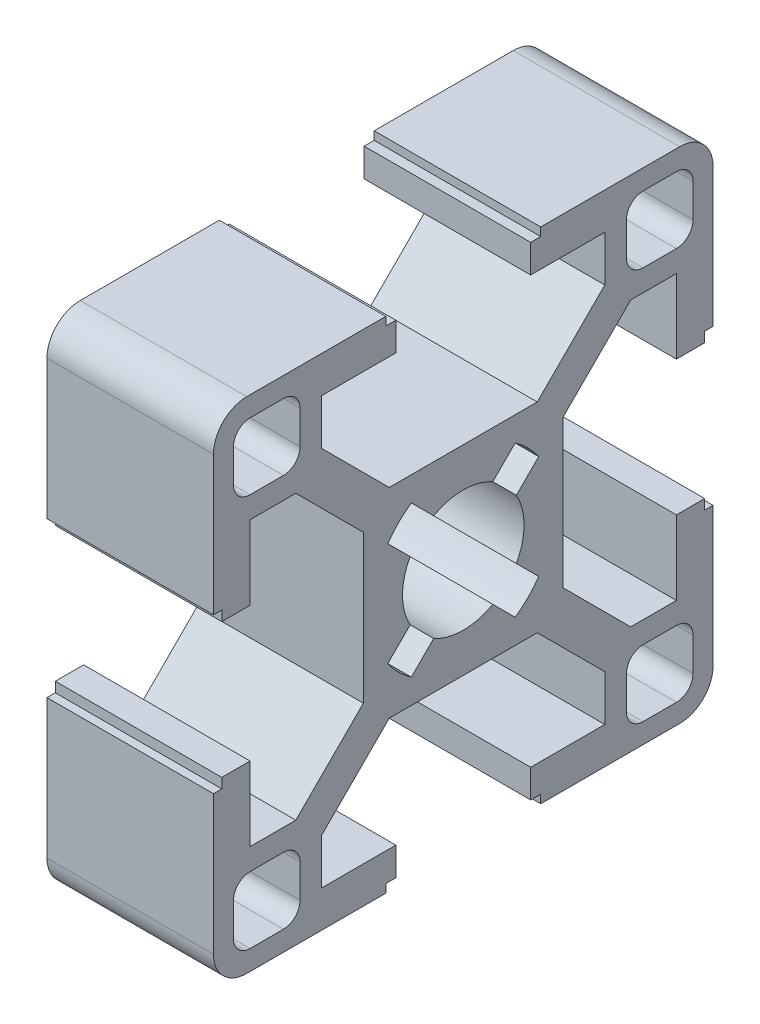
SolidWorks part; units mm, degrees
ref_plane "Ebene vorne" through (0, 0, 0) normal (0, 0, 1) x (1, 0, 0)
ref_plane "Ebene oben" through (0, 0, 0) normal (0, 1, 0) x (1, 0, 0)
ref_plane "Ebene rechts" through (0, 0, 0) normal (1, 0, 0) x (0, 0, -1)
sketch "Skizze1" plane through (0, 0, 0) normal (1, 0, 0) x (0, 0, -1)
  line L0 (8.5, 10.0556) -> (4.4444, 6)
  line L1 (13, 15) -> (-13, 15)
  line L2 (15, 13) -> (15, -13)
  line L3 (13, -15) -> (-13, -15)
  line L4 (-15, 13) -> (-15, -13)
  line L5 (15, 15) -> (-15, -15) construction
  line L6 (15, -15) -> (-15, 15) construction
  line L7 (6, 6) -> (-6, 6)
  line L8 (6, 6) -> (6, -6)
  line L9 (6, -6) -> (-6, -6)
  line L10 (-6, 6) -> (-6, -6)
  line L11 (6, 6) -> (-6, -6) construction
  line L12 (6, -6) -> (-6, 6) construction
  line L13 (8.5, 12.8) -> (-8.5, 12.8)
  line L14 (8.5, 12.8) -> (8.5, 6)
  line L15 (8.5, 6) -> (-8.5, 6)
  line L16 (-8.5, 12.8) -> (-8.5, 6)
  line L17 (4.05, 15) -> (-4.05, 15)
  line L18 (4.05, 15) -> (4.05, 12.8)
  line L19 (4.05, 12.8) -> (-4.05, 12.8)
  line L20 (-4.05, 15) -> (-4.05, 12.8)
  line L21 (-8.5, 10.0556) -> (-4.4444, 6)
  line L22 (3.1172, 4.5314) -> (1.7751, 3.1893)
  line L23 (-3.1172, 4.5314) -> (-1.7751, 3.1893)
  line L24 (15, -4.05) -> (12.8, -4.05)
  line L25 (4.05, 15) -> (4.6516, 15)
  line L26 (4.05, 15) -> (4.05, 14.5)
  line L27 (4.05, 14.5) -> (4.6516, 14.5)
  line L28 (4.6516, 15) -> (4.6516, 14.5)
  line L29 (-4.05, 15) -> (-4.6516, 15)
  line L30 (-4.05, 15) -> (-4.05, 14.5)
  line L31 (-4.05, 14.5) -> (-4.6516, 14.5)
  line L32 (-4.6516, 15) -> (-4.6516, 14.5)
  line L33 (15, -4.6516) -> (14.5, -4.6516)
  line L34 (14.5, -4.05) -> (14.5, -4.6516)
  line L35 (14.5, 4.05) -> (14.5, 4.6516)
  line L36 (15, 4.6516) -> (14.5, 4.6516)
  line L37 (15, 4.05) -> (12.8, 4.05)
  line L38 (12.8, 8.5) -> (6, 8.5)
  line L39 (12.8, -8.5) -> (12.8, 8.5)
  line L40 (12.8, -8.5) -> (6, -8.5)
  line L41 (10.0556, -8.5) -> (6, -4.4444)
  line L42 (10.0556, 8.5) -> (6, 4.4444)
  line L43 (4.5314, -3.1172) -> (3.1893, -1.7751)
  line L44 (4.5314, 3.1172) -> (3.1893, 1.7751)
  line L45 (-4.05, -15) -> (-4.05, -12.8)
  line L46 (-4.6516, -15) -> (-4.6516, -14.5)
  line L47 (-4.05, -14.5) -> (-4.6516, -14.5)
  line L48 (4.05, -14.5) -> (4.6516, -14.5)
  line L49 (4.6516, -15) -> (4.6516, -14.5)
  line L50 (4.05, -15) -> (4.05, -12.8)
  line L51 (8.5, -12.8) -> (8.5, -6)
  line L52 (-8.5, -12.8) -> (8.5, -12.8)
  line L53 (-8.5, -12.8) -> (-8.5, -6)
  line L54 (-8.5, -10.0556) -> (-4.4444, -6)
  line L55 (8.5, -10.0556) -> (4.4444, -6)
  line L56 (-3.1172, -4.5314) -> (-1.7751, -3.1893)
  line L57 (3.1172, -4.5314) -> (1.7751, -3.1893)
  line L58 (-15, 4.05) -> (-12.8, 4.05)
  line L59 (-15, 4.6516) -> (-14.5, 4.6516)
  line L60 (-14.5, 4.05) -> (-14.5, 4.6516)
  line L61 (-14.5, -4.05) -> (-14.5, -4.6516)
  line L62 (-15, -4.6516) -> (-14.5, -4.6516)
  line L63 (-15, -4.05) -> (-12.8, -4.05)
  line L64 (-12.8, -8.5) -> (-6, -8.5)
  line L65 (-12.8, 8.5) -> (-12.8, -8.5)
  line L66 (-12.8, 8.5) -> (-6, 8.5)
  line L67 (-10.0556, 8.5) -> (-6, 4.4444)
  line L68 (-10.0556, -8.5) -> (-6, -4.4444)
  line L69 (-4.5314, 3.1172) -> (-3.1893, 1.7751)
  line L70 (-4.5314, -3.1172) -> (-3.1893, -1.7751)
  line L71 (6, -8.5) -> (6, 8.5)
  line L72 (-8.5, -6) -> (8.5, -6)
  line L73 (-6, 8.5) -> (-6, -8.5)
  line L75 (12.8, 13.8) -> (10.8, 13.8)
  line L76 (13.8, 12.8) -> (13.8, 10.8)
  line L77 (12.8, 9.8) -> (10.8, 9.8)
  line L78 (9.8, 12.8) -> (9.8, 10.8)
  line L79 (13.8, 13.8) -> (9.8, 9.8) construction
  line L80 (13.8, 9.8) -> (9.8, 13.8) construction
  line L81 (-10.8, 13.8) -> (-12.8, 13.8)
  line L82 (-9.8, 12.8) -> (-9.8, 10.8)
  line L83 (-10.8, 9.8) -> (-12.8, 9.8)
  line L84 (-13.8, 12.8) -> (-13.8, 10.8)
  line L85 (-9.8, 13.8) -> (-13.8, 9.8) construction
  line L86 (-9.8, 9.8) -> (-13.8, 13.8) construction
  line L87 (12.8, -9.8) -> (10.8, -9.8)
  line L88 (13.8, -10.8) -> (13.8, -12.8)
  line L89 (12.8, -13.8) -> (10.8, -13.8)
  line L90 (9.8, -10.8) -> (9.8, -12.8)
  line L91 (13.8, -9.8) -> (9.8, -13.8) construction
  line L92 (13.8, -13.8) -> (9.8, -9.8) construction
  line L93 (-10.8, -9.8) -> (-12.8, -9.8)
  line L94 (-9.8, -10.8) -> (-9.8, -12.8)
  line L95 (-10.8, -13.8) -> (-12.8, -13.8)
  line L96 (-13.8, -10.8) -> (-13.8, -12.8)
  line L97 (-9.8, -9.8) -> (-13.8, -13.8) construction
  line L98 (-9.8, -13.8) -> (-13.8, -9.8) construction
  arc A0 (13, -15) -> (15, -13) centre (13, -13) ccw
  arc A1 (-13, -15) -> (-15, -13) centre (-13, -13) cw
  arc A2 (-15, 13) -> (-13, 15) centre (-13, 13) cw
  arc A3 (13, 15) -> (15, 13) centre (13, 13) cw
  circle A4 centre (0, 0) radius 3.65
  circle A5 centre (0, 0) radius 5.5
  circle A6 centre (0, 0) radius 3.65
  circle A7 centre (0, 0) radius 3.65
  circle A8 centre (0, 0) radius 3.65
  arc A9 (12.8, -13.8) -> (13.8, -12.8) centre (12.8, -12.8) ccw
  arc A10 (13.8, -10.8) -> (12.8, -9.8) centre (12.8, -10.8) ccw
  arc A11 (9.8, -12.8) -> (10.8, -13.8) centre (10.8, -12.8) ccw
  arc A12 (9.8, -10.8) -> (10.8, -9.8) centre (10.8, -10.8) cw
  arc A13 (-10.8, -13.8) -> (-9.8, -12.8) centre (-10.8, -12.8) ccw
  arc A14 (-10.8, -9.8) -> (-9.8, -10.8) centre (-10.8, -10.8) cw
  arc A15 (-13.8, -12.8) -> (-12.8, -13.8) centre (-12.8, -12.8) ccw
  arc A16 (-13.8, -10.8) -> (-12.8, -9.8) centre (-12.8, -10.8) cw
  arc A17 (-12.8, 9.8) -> (-13.8, 10.8) centre (-12.8, 10.8) cw
  arc A18 (-10.8, 9.8) -> (-9.8, 10.8) centre (-10.8, 10.8) ccw
  arc A19 (-13.8, 12.8) -> (-12.8, 13.8) centre (-12.8, 12.8) cw
  arc A20 (-10.8, 13.8) -> (-9.8, 12.8) centre (-10.8, 12.8) cw
  arc A21 (13.8, 10.8) -> (12.8, 9.8) centre (12.8, 10.8) cw
  arc A22 (10.8, 9.8) -> (9.8, 10.8) centre (10.8, 10.8) cw
  arc A23 (10.8, 13.8) -> (9.8, 12.8) centre (10.8, 12.8) ccw
  arc A24 (12.8, 13.8) -> (13.8, 12.8) centre (12.8, 12.8) cw
  point P0 (0, 0)
  point P33 (0, 12.8)
  point P34 (0, 15)
  point P36 (0, 12.8)
  point P50 (11.8, 11.8)
  point P122 (0, 0)
  point P125 (-11.8, 11.8)
  point P129 (0, 0)
  point P131 (11.8, -11.8)
  point P136 (-11.8, -11.8)
  point P141 (0, 0)
  point P142 (0, 0)
  point P143 (0, 0)
  point P144 (0, 0)
  dimension "D2" = 2
  dimension "D3" = 7.3
  dimension "D4" = 11
  dimension "D20" = 1
  dimension "D1" = 30
  dimension "D5" = 12
  dimension "D6" = 17
  dimension "D7" = 8.1
  dimension "D8" = 2.2
  dimension "D9" = 9
  dimension "D10" = 1.1
  dimension "D11" = 1.1
  dimension "D12" = 1
  dimension "D13" = 1
  dimension "D14" = 0.5
  dimension "D15" = 0.6016
  dimension "D18" = 4
  dimension "D19" = 1.2
  dimension "D16" = 4
  dimension "D17" = 4
extrude "Aufsatz-Linear austragen1" add sketch "Skizze1" along normal blind 10 contours A3 L1 L28 L27 L18 L13 L14 L38 L39 L37 L35 L36 L2 | L42 L38 L14 | L71 L15 L42 L14 L38 L0 | L42 L15 L8 | L7 L71 L0 | L38 L14 L0 | L7 L15 L10 L9 L8 A5 | L43 A5 L44 A4 | L22 A5 L23 A4 | L69 A5 L70 A4 | L56 A5 L57 A4 | L3 A0 L2 L33 L34 L24 L39 L40 L51 L52 L50 L48 L49 | L51 L40 L41 | L72 L71 L55 L40 L51 L41 | L8 L72 L41 | L55 L71 L9 | L55 L51 L40 | L73 L72 L68 L53 L64 L54 | L68 L72 L10 | L9 L73 L54 | L68 L64 L53 | L64 L53 L54 | A1 L3 L46 L47 L45 L52 L53 L64 L65 L63 L61 L62 L4 | A2 L4 L59 L60 L58 L65 L66 L16 L13 L20 L31 L32 L1 | L66 L67 L16 | L16 L66 L21 | L73 L21 L66 L16 L67 L15 | L21 L73 L15 | L15 L67 L10
